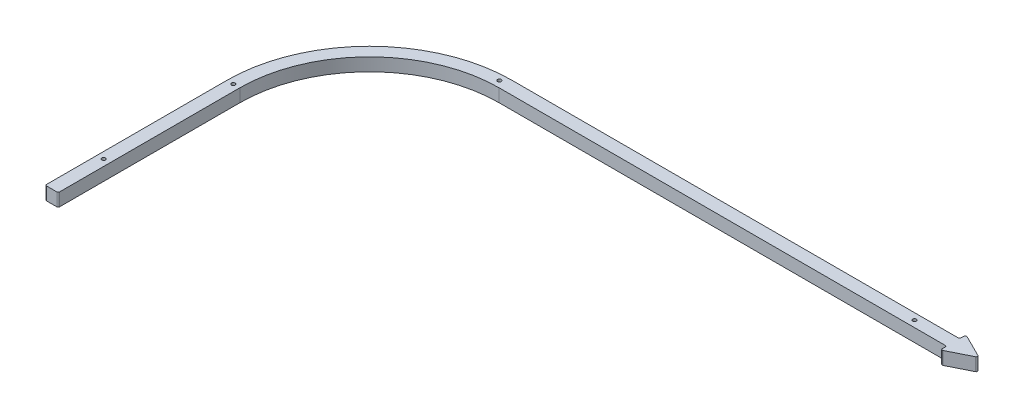
SolidWorks part; units mm, degrees
material "Acrylic (Medium-high impact)"
ref_plane "Front" through (0, 0, 0) normal (0, 0, 1) x (1, 0, 0)
ref_plane "Top" through (0, 0, 0) normal (0, 1, 0) x (1, 0, 0)
ref_plane "Right" through (0, 0, 0) normal (1, 0, 0) x (0, 0, -1)
sketch "Sketch1" plane through (0, 0, 0) normal (0, 1, 0) x (1, 0, 0)
  line L0 (69.85, 158.75) -> (69.85, 152.4)
  line L1 (0, 0) -> (6.35, 0)
  line L2 (0, 0) -> (0, 88.9)
  line L3 (0, 88.9) -> (6.35, 88.9)
  line L4 (6.35, 0) -> (6.35, 88.9)
  line L9 (69.85, 158.75) -> (301.625, 158.75)
  line L10 (69.85, 152.4) -> (301.625, 152.4)
  line L11 (301.625, 158.75) -> (301.625, 152.4)
  line L12 (288.925, 161.925) -> (301.625, 155.575)
  line L13 (288.925, 149.225) -> (301.625, 149.225)
  line L14 (288.925, 149.225) -> (288.925, 161.925)
  line L15 (288.925, 161.925) -> (301.625, 161.925)
  line L16 (301.625, 149.225) -> (301.625, 161.925)
  line L17 (301.625, 155.575) -> (288.925, 149.225)
  arc A0 (6.35, 88.9) -> (69.85, 152.4) centre (69.85, 88.9) cw
  arc A1 (0, 88.9) -> (69.85, 158.75) centre (69.85, 88.9) cw
  point P14 (301.625, 155.575)
  dimension "D1" = 6.35
  dimension "D2" = 88.9
  dimension "D3" = 231.775
  dimension "D4" = 63.5
  dimension "D5" = 12.7
  dimension "D6" = 12.7
  dimension "D7" = 6.35
extrude "Boss-Extrude1" add sketch "Sketch1" along normal blind 6.35 contours L1 L4 L3 L2 | A1 L3 A0 L0 | L11 L9 L0 L10 | L14 L13 L16 L15
sketch "Sketch2" plane through (0, 6.35, 0) normal (0, 1, 0) x (1, 0, 0)
  line L0 (288.925, 161.925) -> (301.625, 155.575)
  line L1 (301.625, 149.225) -> (301.625, 161.925) construction
  line L2 (301.625, 155.575) -> (288.925, 149.225)
  line L3 (288.925, 161.925) -> (301.625, 161.925) construction
extrude "Cut-Extrude1" cut sketch "Sketch2" against normal through all and the other way through all
fillet "Fillet1" radius 0.635 7 edges at (0, 3.175, 0) (6.35, 3.175, 0) (288.925, 3.175, -149.225) (288.925, 3.175, -152.4) (301.625, 3.175, -155.575) (288.925, 3.175, -161.925) (288.925, 3.175, -158.75)
sketch "Sketch3" plane through (0, 6.35, 0) normal (0, 1, 0) x (1, 0, 0)
  line L0 (3.175, 0) -> (3.175, 88.9) construction
  line L1 (0.635, 0) -> (5.715, 0) construction
  line L2 (300.8401, 155.575) -> (68.9959, 155.575) construction
  arc A0 (300.4891, 155.007) -> (300.4891, 156.143) centre (300.2051, 155.575) ccw construction
  circle A1 centre (3.175, 25.4) radius 0.889
  circle A2 centre (3.175, 88.9) radius 0.889
  circle A3 centre (66.802, 155.575) radius 0.889
  circle A4 centre (270.002, 155.575) radius 0.889
  dimension "D1" = 1.778
  dimension "D2" = 25.4
  dimension "D4" = 1.778
  dimension "D5" = 63.627
  dimension "D3" = 2
  dimension "D6" = 2
extrude "Cut-Extrude2" cut sketch "Sketch3" against normal through all
